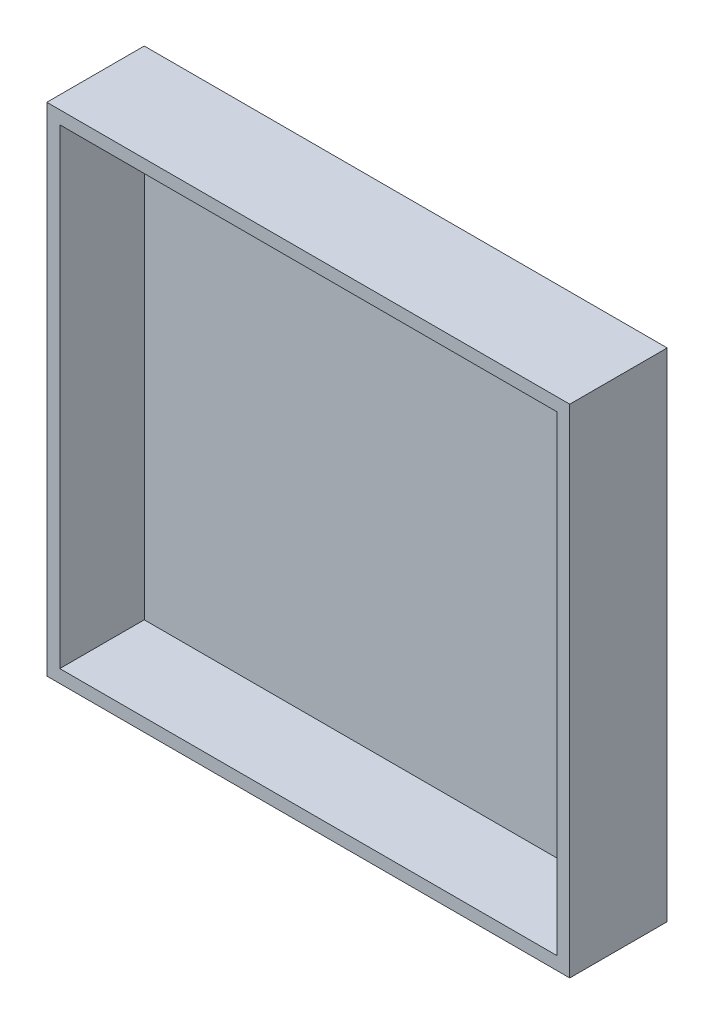
SolidWorks part; units mm, degrees
ref_plane "Plan de face" through (0, 0, 0) normal (0, 0, 1) x (1, 0, 0)
ref_plane "Plan de dessus" through (0, 0, 0) normal (0, 1, 0) x (1, 0, 0)
ref_plane "Plan de droite" through (0, 0, 0) normal (1, 0, 0) x (0, 0, -1)
sketch "Esquisse1" plane through (0, 0, 0) normal (0, 0, 1) x (1, 0, 0)
  line L1 (-70.1386, 46.5558) -> (10.3614, 46.5558)
  line L2 (-70.1386, 46.5558) -> (-70.1386, -29.9442)
  line L3 (-70.1386, -29.9442) -> (10.3614, -29.9442)
  line L4 (10.3614, 46.5558) -> (10.3614, -29.9442)
  dimension "D1" = 76.5
  dimension "D2" = 80.5
extrude "Boss.-Extru.1" add sketch "Esquisse1" along normal blind 2
sketch "Esquisse2" plane through (0, 0, 2) normal (0, 0, 1) x (1, 0, 0)
  line L1 (-70.1386, 46.5558) -> (10.3614, 46.5558)
  line L2 (-70.1386, 46.5558) -> (-70.1386, -29.9442)
  line L3 (-70.1386, -29.9442) -> (10.3614, -29.9442)
  line L4 (10.3614, 46.5558) -> (10.3614, -29.9442)
  line L5 (-68.1386, 44.5558) -> (8.3614, 44.5558)
  line L6 (-68.1386, 44.5558) -> (-68.1386, -27.9442)
  line L7 (-68.1386, -27.9442) -> (8.3614, -27.9442)
  line L8 (8.3614, 44.5558) -> (8.3614, -27.9442)
  dimension "D1" = 2
  dimension "D2" = 2
  dimension "D3" = 2
  dimension "D4" = 2
extrude "Boss.-Extru.2" add sketch "Esquisse2" along normal blind 13
sketch "Esquisse4" plane through (0, 0, 15) normal (0, 0, 1) x (1, 0, 0)
  line L0 (-68.1386, -27.9442) -> (8.3614, -27.9442) construction
  line L1 (-74.9001, -17.9442) -> (-62.4118, -17.9442)
  line L2 (-74.9001, -17.9442) -> (-74.9001, -9.9442)
  line L3 (-74.9001, -9.9442) -> (-62.4118, -9.9442)
  line L4 (-62.4118, -17.9442) -> (-62.4118, -9.9442)
  line L7 (-62.4118, 14.0558) -> (-74.278, 14.0558)
  line L8 (-62.4118, 14.0558) -> (-62.4118, 3.0558)
  line L9 (-62.4118, 3.0558) -> (-74.278, 3.0558)
  line L10 (-74.278, 14.0558) -> (-74.278, 3.0558)
  line L11 (-64.9729, 34.0558) -> (-76.918, 34.0558)
  line L12 (-64.9729, 34.0558) -> (-64.9729, 20.0558)
  line L13 (-64.9729, 20.0558) -> (-76.918, 20.0558)
  line L14 (-76.918, 34.0558) -> (-76.918, 20.0558)
  dimension "D1" = 10
  dimension "D2" = 8
  dimension "D3" = 11
  dimension "D4" = 31
  dimension "D5" = 48
  dimension "D6" = 14
